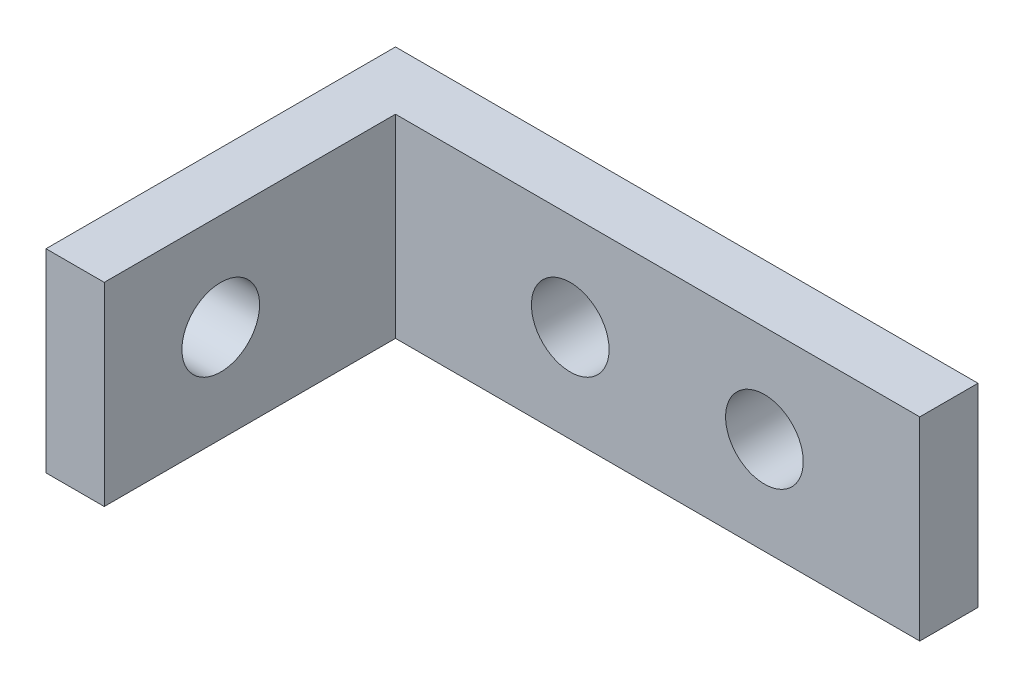
SolidWorks part; units mm, degrees
material "Stainless Steel (ferritic)"
ref_plane "Front Plane" through (0, 0, 0) normal (0, 0, 1) x (1, 0, 0)
ref_plane "Top Plane" through (0, 0, 0) normal (0, 1, 0) x (1, 0, 0)
ref_plane "Right Plane" through (0, 0, 0) normal (1, 0, 0) x (0, 0, -1)
sketch "Sketch2" plane through (0, 0, 0) normal (0, 0, 1) x (1, 0, 0)
  line L1 (0, 0) -> (30, 0)
  line L2 (0, 0) -> (0, 10)
  line L3 (0, 10) -> (30, 10)
  line L4 (30, 0) -> (30, 10)
  circle A0 centre (12, 5) radius 2
  circle A1 centre (22, 5) radius 2
  dimension "D3" = 4
  dimension "D4" = 4
  dimension "D5" = 5
  dimension "D6" = 5
  dimension "D7" = 12
  dimension "D8" = 10
  dimension "D1" = 30
  dimension "D2" = 10
extrude "Boss-Extrude1" add sketch "Sketch2" along normal blind 3
sketch "Sketch3" plane through (0, 0, 3) normal (0, 0, 1) x (1, 0, 0)
  line L0 (0, 0) -> (30, 0) construction
  line L1 (0, 10) -> (3, 10)
  line L2 (0, 10) -> (0, 0)
  line L3 (0, 0) -> (3, 0)
  line L4 (3, 10) -> (3, 0)
  dimension "D1" = 3
extrude "Boss-Extrude2" add sketch "Sketch3" along normal blind 15
sketch "Sketch4" plane through (3, 0, 0) normal (1, 0, 0) x (0, 0, -1)
  line L0 (0, 0) -> (0, 10) construction
  line L1 (-18, 10) -> (-3, 10) construction
  circle A0 centre (-22, 5) radius 2
  circle A1 centre (-12, 5) radius 2
  dimension "D1" = 4
  dimension "D2" = 4
  dimension "D3" = 12
  dimension "D4" = 10
  dimension "D5" = 5
  dimension "D6" = 5
extrude "Cut-Extrude1" cut sketch "Sketch4" against normal blind 27
